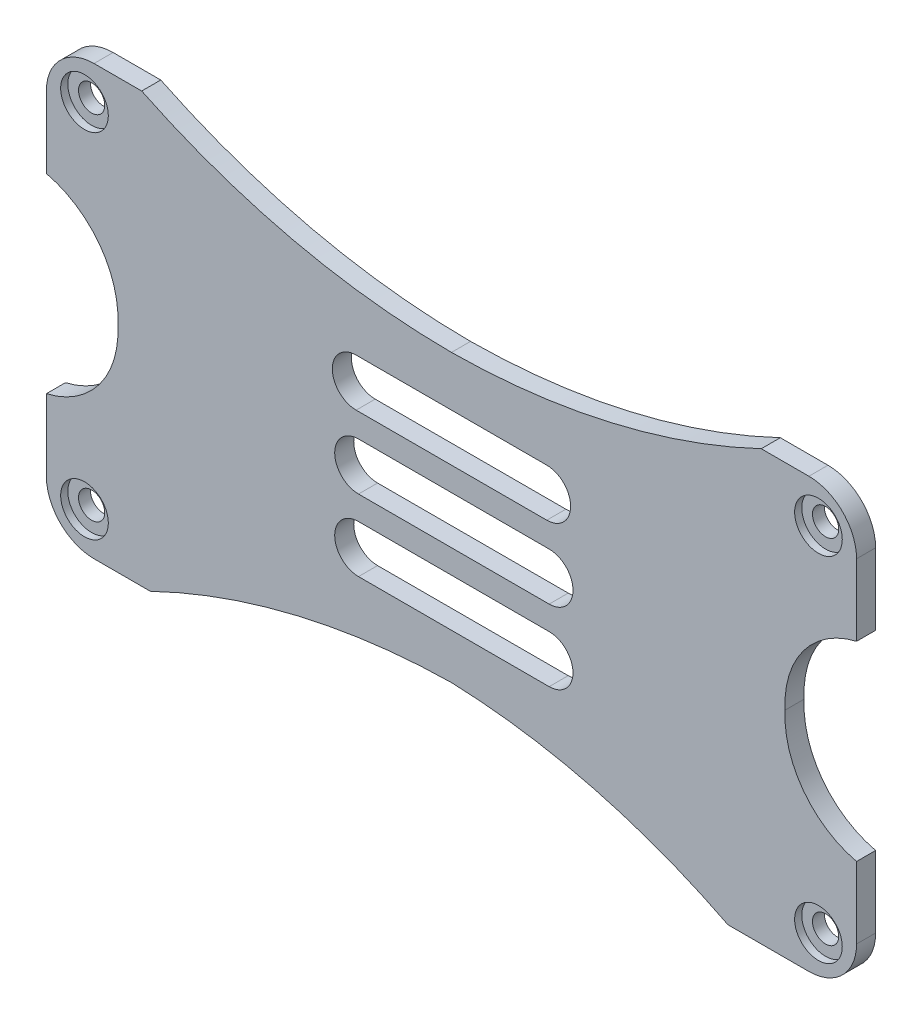
SolidWorks part; units mm, degrees
ref_plane "前视基准面" through (0, 0, 0) normal (0, 0, 1) x (1, 0, 0)
ref_plane "上视基准面" through (0, 0, 0) normal (0, 1, 0) x (1, 0, 0)
ref_plane "右视基准面" through (0, 0, 0) normal (1, 0, 0) x (0, 0, -1)
sketch "草图1" plane through (0, 0, 0) normal (0, 0, 1) x (1, 0, 0)
  line L1 (-72.5741, 45.4874) -> (77.4259, 45.4874)
  line L2 (-82.5741, 35.4874) -> (-82.5741, -34.5126)
  line L3 (-72.5741, -44.5126) -> (77.4259, -44.5126)
  line L4 (87.4259, 35.4874) -> (87.4259, -34.5126)
  arc A0 (-72.5741, 45.4874) -> (-82.5741, 35.4874) centre (-72.5741, 35.4874) ccw
  arc A1 (-72.5741, -44.5126) -> (-82.5741, -34.5126) centre (-72.5741, -34.5126) cw
  arc A2 (87.4259, 35.4874) -> (77.4259, 45.4874) centre (77.4259, 35.4874) ccw
  arc A3 (87.4259, -34.5126) -> (77.4259, -44.5126) centre (77.4259, -34.5126) cw
  dimension "D1" = 10
  dimension "D2" = 10
  dimension "D3" = 10
  dimension "D4" = 10
  dimension "D5" = 90
  dimension "D6" = 170
extrude "凸台-拉伸1" add sketch "草图1" along normal blind 4
ref_plane "for screw hole" through (0, 0, 4) normal (0, 0, 1) x (1, 0, 0)
sketch "草图2" plane through (0, 0, 4) normal (0, 0, 1) x (1, 0, 0)
  line L0 (77.4259, 45.4874) -> (-72.5741, 45.4874) construction
  line L1 (-82.5741, 35.4874) -> (-82.5741, -34.5126) construction
  line L2 (-72.5741, -44.5126) -> (77.4259, -44.5126) construction
  line L3 (87.4259, -34.5126) -> (87.4259, 35.4874) construction
  line L4 (-60.7497, -44.5126) -> (60.4378, -44.5126)
  line L5 (-62.5741, 45.4874) -> (67.4259, 45.4874)
  line L6 (87.4259, 20.4874) -> (87.4259, -19.5126)
  line L7 (-82.5741, 20.4874) -> (-82.5741, -19.5126)
  line L8 (-17.5741, 15) -> (22.4259, 15) construction
  line L9 (-17.5741, 20) -> (22.4259, 20)
  line L10 (-17.5741, 10) -> (22.4259, 10)
  line L11 (-17.0794, 0) -> (22.9206, 0) construction
  line L12 (-17.0794, 5) -> (22.9206, 5)
  line L13 (-17.0794, -5) -> (22.9206, -5)
  line L14 (-17.0794, -15) -> (22.9206, -15) construction
  line L15 (-17.0794, -10) -> (22.9206, -10)
  line L16 (-17.0794, -20) -> (22.9206, -20)
  circle A0 centre (-74.5741, 37.4874) radius 2.75
  circle A1 centre (-74.5741, -36.5126) radius 2.75
  circle A2 centre (79.4259, 37.4874) radius 2.75
  circle A3 centre (79.4259, -36.5126) radius 2.75
  arc A4 (67.4259, 45.4874) -> (2.4259, 30.4874) centre (1.0956, 184.5854) cw
  arc A5 (-62.5741, 45.4874) -> (2.4259, 30.4874) centre (2.8104, 180.4869) ccw
  arc A6 (-60.7497, -44.5126) -> (2.4259, -29.5126) centre (4.6684, -179.4958) cw
  arc A7 (60.4378, -44.5126) -> (2.4259, -29.5126) centre (-2.3985, -167.85) ccw
  arc A8 (87.4259, 20.4874) -> (72.4259, 0.4874) centre (91.8434, 1.5492) ccw
  arc A9 (87.4259, -19.5126) -> (72.4259, 0.4874) centre (91.8434, -0.5745) cw
  arc A10 (-82.5741, 20.4874) -> (-67.5741, 0.4874) centre (-86.9917, 1.5492) cw
  arc A11 (-82.5741, -19.5126) -> (-67.5741, 0.4874) centre (-86.9917, -0.5745) ccw
  arc A12 (-17.5741, 20) -> (-17.5741, 10) centre (-17.5741, 15) ccw
  arc A13 (22.4259, 10) -> (22.4259, 20) centre (22.4259, 15) ccw
  arc A14 (-17.0794, 5) -> (-17.0794, -5) centre (-17.0794, 0) ccw
  arc A15 (22.9206, -5) -> (22.9206, 5) centre (22.9206, 0) ccw
  arc A16 (-17.0794, -10) -> (-17.0794, -20) centre (-17.0794, -15) ccw
  arc A17 (22.9206, -20) -> (22.9206, -10) centre (22.9206, -15) ccw
  point P12 (2.4259, 30.4874)
  point P13 (2.4259, -29.5126)
  point P16 (-62.5741, 45.4874)
  point P17 (67.4259, 45.4874)
  point P18 (-60.7497, -44.5126)
  point P19 (60.4378, -44.5126)
  point P29 (-67.5741, 0.4874)
  point P33 (72.4259, 0.4874)
  point P34 (-82.5741, 20.4874)
  point P35 (-82.5741, -19.5126)
  point P36 (87.4259, -19.5126)
  point P37 (87.4259, 20.4874)
  point P54 (2.4259, 15)
  point P61 (2.9206, 0)
  point P68 (2.9206, -15)
  dimension "D2" = 5.5
  dimension "D3" = 5.5
  dimension "D4" = 5.5
  dimension "D8" = 8
  dimension "D9" = 8
  dimension "D10" = 8
  dimension "D11" = 5.5
  dimension "D21" = 45
  dimension "D5" = 8
  dimension "D6" = 8
  dimension "D7" = 8
  dimension "D12" = 8
  dimension "D13" = 8
  dimension "D14" = 85
  dimension "D15" = 15
  dimension "D16" = 85
  dimension "D17" = 15
  dimension "D18" = 20
  dimension "D19" = 20
  dimension "D20" = 26.9881
  dimension "D22" = 15
  dimension "D23" = 15
  dimension "D24" = 45
  dimension "D25" = 25
  dimension "D26" = 25
  dimension "D27" = 25
  dimension "D28" = 25
  dimension "D31" = 15
extrude "切除-拉伸1" cut sketch "草图2" against normal blind 10 and the other way blind 42
ref_plane "for outer screw hole" through (0, 0, 4) normal (0, 0, 1) x (1, 0, 0)
sketch "草图3" plane through (0, 0, 4) normal (0, 0, 1) x (1, 0, 0)
  circle A0 centre (-74.5741, 37.4874) radius 5
  circle A1 centre (79.4259, 37.4874) radius 5
  circle A2 centre (79.4259, -36.5126) radius 5
  circle A3 centre (-74.5741, -36.5126) radius 5
  dimension "D1" = 10
  dimension "D2" = 10
  dimension "D3" = 10
  dimension "D4" = 10
extrude "切除-拉伸2" cut sketch "草图3" against normal blind 1.5
